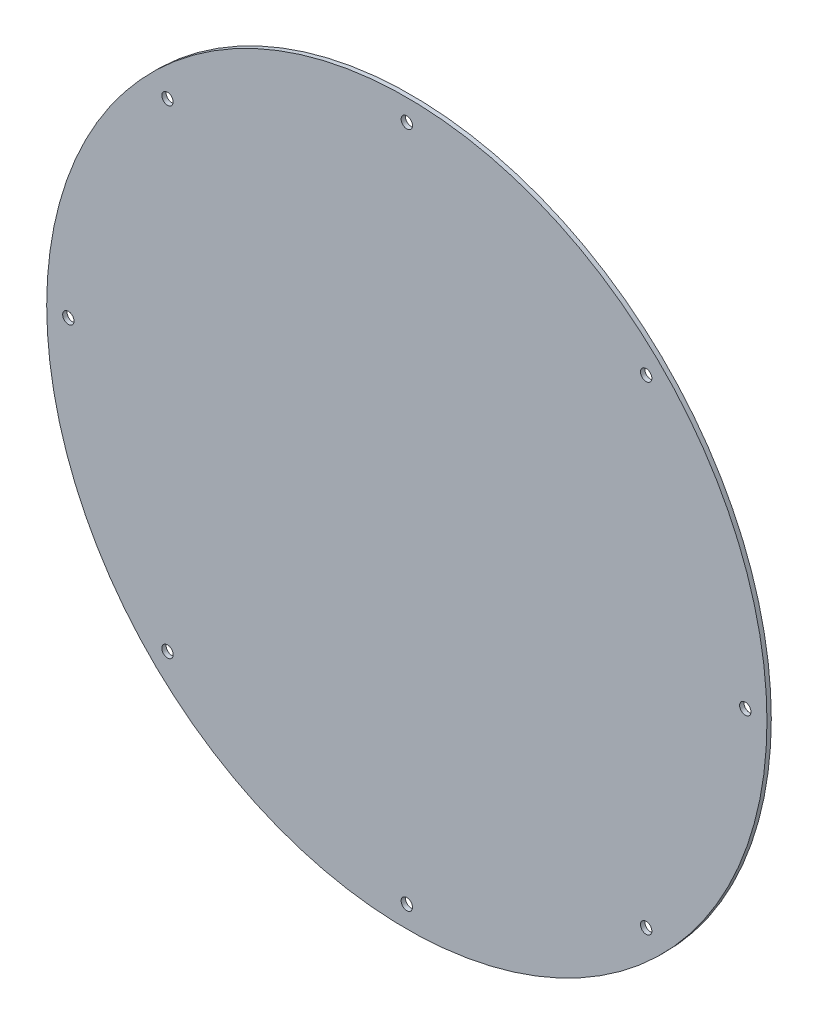
SolidWorks part; units mm, degrees
ref_plane "Ön Düzlem" through (0, 0, 0) normal (0, 0, 1) x (1, 0, 0)
ref_plane "Üst Düzlem" through (0, 0, 0) normal (0, 1, 0) x (1, 0, 0)
ref_plane "Sağ Düzlem" through (0, 0, 0) normal (1, 0, 0) x (0, 0, -1)
sketch "Sketch1" plane through (0, 0, 0) normal (0, 0, 1) x (1, 0, 0)
  line L0 (0, 0) -> (0, 125) construction
  circle A0 centre (0, 0) radius 133
  circle A1 centre (0, 125) radius 2.1
  circle A2 centre (88.3883, 88.3883) radius 2.1
  circle A3 centre (125, 0) radius 2.1
  circle A4 centre (88.3883, -88.3883) radius 2.1
  circle A5 centre (0, -125) radius 2.1
  circle A6 centre (-88.3883, -88.3883) radius 2.1
  circle A7 centre (-125, 0) radius 2.1
  circle A8 centre (-88.3883, 88.3883) radius 2.1
  point P21 (0, 0)
  dimension "D1" = 266
  dimension "D3" = 8
  dimension "D2" = 125
extrude "Boss-Extrude2" add sketch "Sketch1" along normal blind 1.6
